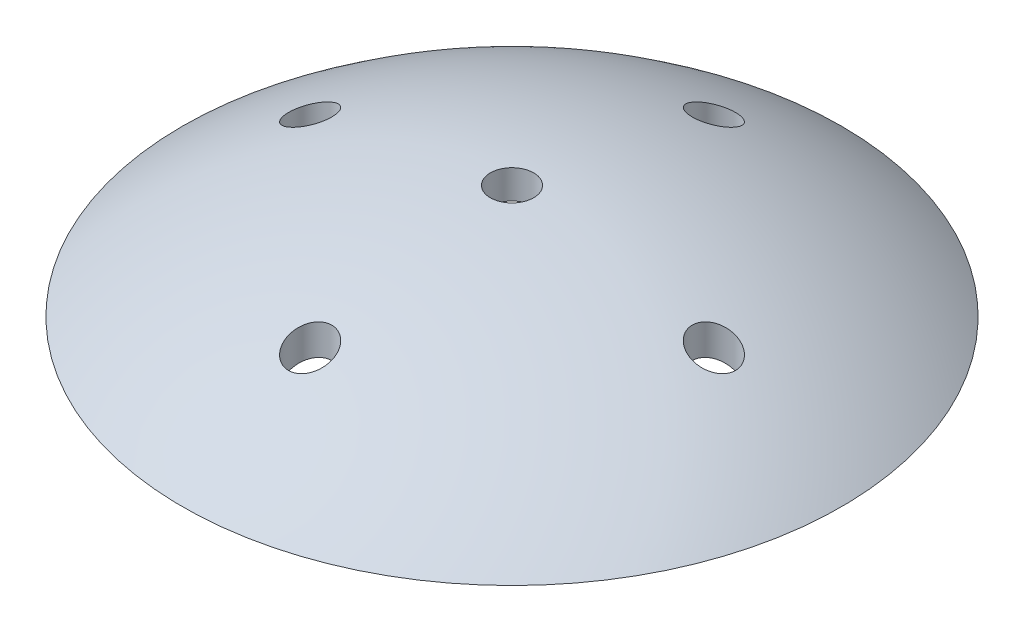
SolidWorks part; units mm, degrees
ref_plane "Front Plane" through (0, 0, 0) normal (0, 0, 1) x (1, 0, 0)
ref_plane "Top Plane" through (0, 0, 0) normal (0, 1, 0) x (1, 0, 0)
ref_plane "Right Plane" through (0, 0, 0) normal (1, 0, 0) x (0, 0, -1)
sketch "Sketch1" plane through (0, 0, 0) normal (0, 0, 1) x (1, 0, 0)
  line L0 (0, 37) -> (0, 0)
  line L1 (0, 0) -> (0, -37)
  line L2 (0, 51.7877) -> (0, -60.5028) construction
  arc A0 (0, 37) -> (0, -37) centre (0, 0) ccw
  dimension "D1" = 37
revolve "Revolve1" add sketch "Sketch1" angle 360 about L2
sketch "Sketch3" plane through (0, 0, 0) normal (0, 0, 1) x (1, 0, 0)
  line L0 (-46.086, 29.0937) -> (-46.086, -39.884)
  line L1 (-46.086, -39.884) -> (50.4223, -39.884)
  line L2 (50.4223, -39.884) -> (50.4223, 29.0937)
  line L3 (50.4223, 29.0937) -> (-46.086, 29.0937)
extrude "Cut-Extrude1" cut sketch "Sketch3" against normal mid plane 200
sketch "Sketch4" plane through (0, 0, 0) normal (0, 0, 1) x (1, 0, 0)
  line L0 (0, 0) -> (0, 35)
  line L1 (0, 0) -> (0, -35)
  line L2 (0, 39.939) -> (0, -32.064) construction
  arc A0 (0, -35) -> (0, 35) centre (0, 0) cw
  dimension "D1" = 35
revolve "Cut-Revolve1" cut sketch "Sketch4" angle 360 about L2
sketch "Sketch5" plane through (0, 0, 0) normal (0, 1, 0) x (1, 0, 0)
  circle A0 centre (0, 14) radius 1.5
  circle A1 centre (14, 0) radius 1.5
  circle A2 centre (0, -14) radius 1.5
  circle A3 centre (-14, 0) radius 1.5
  dimension "D1" = 3
  dimension "D2" = 14
  dimension "D4" = 14
  dimension "D3" = 14
  dimension "D5" = 14
extrude "Cut-Extrude2" cut sketch "Sketch5" against normal mid plane 200
sketch "Sketch6" plane through (0, 0, 0) normal (0, 1, 0) x (1, 0, 0)
  circle A0 centre (0, 0) radius 1.5
  dimension "D1" = 3
extrude "Cut-Extrude3" cut sketch "Sketch6" against normal mid plane 200
